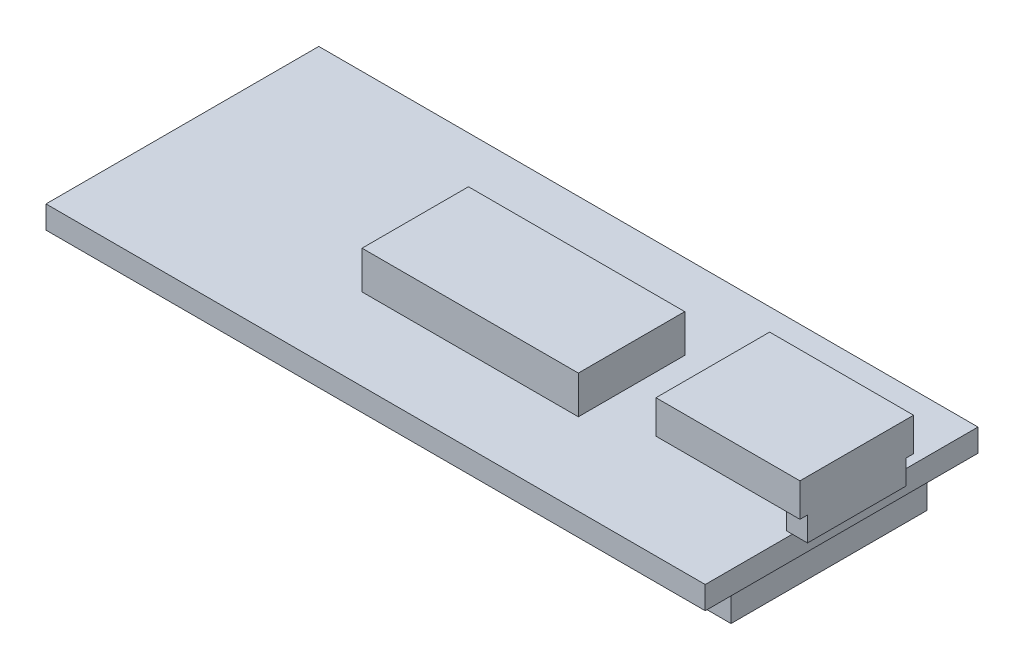
SolidWorks part; units mm, degrees
ref_plane "Спереди" through (0, 0, 0) normal (0, 0, 1) x (1, 0, 0)
ref_plane "Сверху" through (0, 0, 0) normal (0, 1, 0) x (1, 0, 0)
ref_plane "Справа" through (0, 0, 0) normal (1, 0, 0) x (0, 0, -1)
sketch "Эскиз1" plane through (0, 0, 0) normal (0, 1, 0) x (1, 0, 0)
  line L1 (0, 0) -> (43.5, 0)
  line L2 (0, 0) -> (0, 18)
  line L3 (0, 18) -> (43.5, 18)
  line L4 (43.5, 0) -> (43.5, 18)
  dimension "D1" = 18
  dimension "D2" = 43.5
extrude "Бобышка-Вытянуть1" add sketch "Эскиз1" along normal blind 1.5
sketch "Эскиз2" plane through (0, 1.5, 0) normal (0, 1, 0) x (1, 0, 0)
  line L0 (43.5, 0) -> (43.5, 18) construction
  line L1 (43.1236, 5.75) -> (44.5, 5.75)
  line L2 (43.1236, 5.75) -> (43.1236, 12.25)
  line L3 (43.1236, 12.25) -> (44.5, 12.25)
  line L4 (44.5, 5.75) -> (44.5, 12.25)
  dimension "D1" = 6.5
  dimension "D2" = 1
  dimension "D3" = 5.75
sketch3d "Трехмерный эскиз1" plane through (0, 0, 0) normal (0, 0, 1) x (1, 0, 0)
extrude "Бобышка-Вытянуть2" add sketch "Эскиз2" along normal blind 3.8 contours L2 L1 L4 L3
sketch "Эскиз3" plane through (0, 5.3, 0) normal (0, 1, 0) x (1, 0, 0)
  line L1 (35, 12.75) -> (44.5, 12.75)
  line L2 (35, 12.75) -> (35, 5.25)
  line L3 (35, 5.25) -> (44.5, 5.25)
  line L4 (44.5, 12.75) -> (44.5, 5.25)
  line L5 (44.5, 5.75) -> (44.5, 12.25) construction
  dimension "D1" = 7.5
  dimension "D2" = 0.5
  dimension "D3" = 9.5
sketch "Эскиз4" plane through (0, 1.5, 0) normal (0, 1, 0) x (1, 0, 0)
sketch "Эскиз6" plane through (0, 1.5, 0) normal (0, 1, 0) x (1, 0, 0)
extrude "Бобышка-Вытянуть7" add sketch "Эскиз3" against normal blind 2.2
sketch "Эскиз8" plane through (0, 0, 0) normal (0, -1, 0) x (-1, 0, 0)
  line L1 (-2.477, 15.5465) -> (-42.5847, 15.5465)
  line L2 (-2.477, 15.5465) -> (-2.477, 2.6182)
  line L3 (-2.477, 2.6182) -> (-42.5847, 2.6182)
  line L4 (-42.5847, 15.5465) -> (-42.5847, 2.6182)
extrude "Бобышка-Вытянуть8" add sketch "Эскиз8" along normal blind 2.5
sketch "Эскиз9" plane through (0, 1.5, 0) normal (0, 1, 0) x (1, 0, 0)
  line L1 (15.4577, 12.4191) -> (29.7307, 12.4191)
  line L2 (15.4577, 12.4191) -> (15.4577, 5.3973)
  line L3 (15.4577, 5.3973) -> (29.7307, 5.3973)
  line L4 (29.7307, 12.4191) -> (29.7307, 5.3973)
extrude "Бобышка-Вытянуть9" add sketch "Эскиз9" along normal blind 2.5 contours L2 L1 L4 L3
